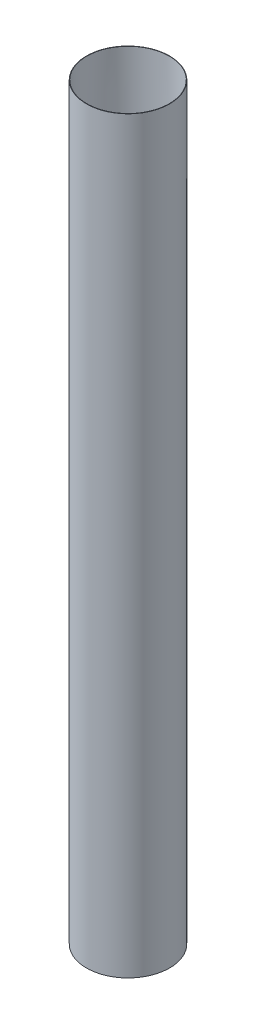
SolidWorks part; units mm, degrees
ref_plane "Front Plane" through (0, 0, 0) normal (0, 0, 1) x (1, 0, 0)
ref_plane "Top Plane" through (0, 0, 0) normal (0, 1, 0) x (1, 0, 0)
ref_plane "Right Plane" through (0, 0, 0) normal (1, 0, 0) x (0, 0, -1)
sketch "Sketch1" plane through (0, 0, 0) normal (0, 0, 1) x (1, 0, 0)
  line L0 (0, 0) -> (4945, 0) construction
  line L1 (4945, 0) -> (5000, 0)
  line L2 (0, 0) -> (0, 90000) construction
  line L3 (0, 90000) -> (4959, 90000) construction
  line L4 (4959, 90000) -> (5000, 90000)
  line L5 (4959, 90000) -> (4945, 0)
  line L6 (5000, 0) -> (5000, 90000)
  dimension "D1" = 4945
  dimension "D2" = 55
  dimension "D3" = 4959
  dimension "D4" = 41
revolve "Revolve1" add sketch "Sketch1" angle 360 about L2
